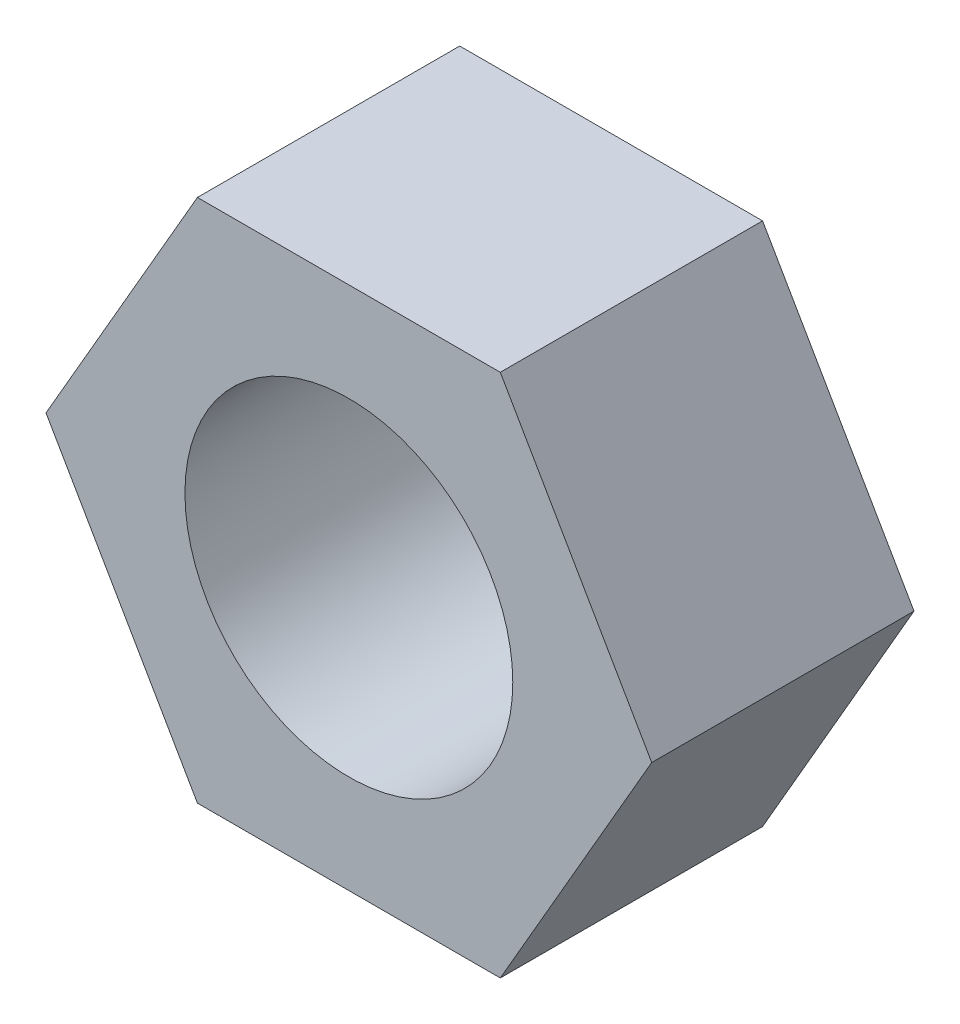
SolidWorks part; units mm, degrees
material "AISI 4340 Steel, normalized"
ref_plane "Front Plane" through (0, 0, 0) normal (0, 0, 1) x (1, 0, 0)
ref_plane "Top Plane" through (0, 0, 0) normal (0, 1, 0) x (1, 0, 0)
ref_plane "Right Plane" through (0, 0, 0) normal (1, 0, 0) x (0, 0, -1)
sketch "Sketch1" plane through (0, 0, 0) normal (0, 0, 1) x (1, 0, 0)
  line L0 (4.6188, 0) -> (2.3094, 4)
  line L1 (2.3094, 4) -> (-2.3094, 4)
  line L2 (-2.3094, 4) -> (-4.6188, 0)
  line L3 (-4.6188, 0) -> (-2.3094, -4)
  line L4 (-2.3094, -4) -> (2.3094, -4)
  line L5 (2.3094, -4) -> (4.6188, 0)
  circle A0 centre (0, 0) radius 2.5
extrude "Nut_Thread_Major_Envelope" add sketch "Sketch1" along normal blind 4
